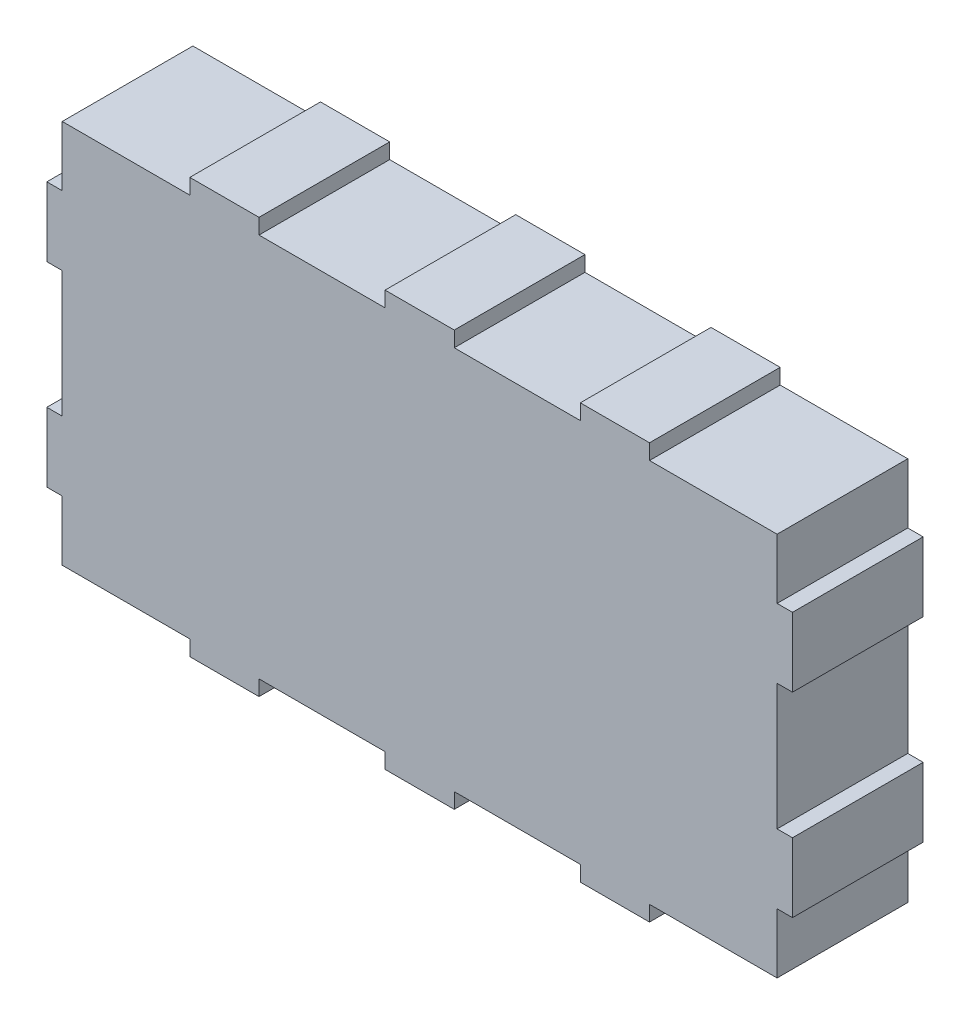
SolidWorks part; units mm, degrees
ref_plane "前视基准面" through (0, 0, 0) normal (0, 0, 1) x (1, 0, 0)
ref_plane "上视基准面" through (0, 0, 0) normal (0, 1, 0) x (1, 0, 0)
ref_plane "右视基准面" through (0, 0, 0) normal (1, 0, 0) x (0, 0, -1)
sketch "草图1" plane through (0, 0, 0) normal (0, 0, 1) x (1, 0, 0)
  line L0 (-4.85, 1.72) -> (-4.65, 1.72)
  line L1 (-4.65, 1.72) -> (-4.65, 2.5)
  line L2 (-4.65, 2.5) -> (-2.99, 2.5)
  line L3 (-2.99, 2.5) -> (-2.99, 2.7)
  line L4 (-2.99, 2.7) -> (-2.09, 2.7)
  line L5 (-2.09, 2.7) -> (-2.09, 2.5)
  line L6 (-2.09, 2.5) -> (-0.45, 2.5)
  line L7 (-0.45, 2.5) -> (-0.45, 2.7)
  line L8 (-0.45, 2.7) -> (0.45, 2.7)
  line L9 (0.45, 2.7) -> (0.45, 2.5)
  line L10 (0.45, 2.5) -> (2.09, 2.5)
  line L11 (2.09, 2.5) -> (2.09, 2.7)
  line L12 (2.09, 2.7) -> (2.99, 2.7)
  line L13 (2.99, 2.7) -> (2.99, 2.5)
  line L14 (2.99, 2.5) -> (4.65, 2.5)
  line L15 (4.65, 2.5) -> (4.65, 1.72)
  line L16 (4.65, 1.72) -> (4.85, 1.72)
  line L17 (4.85, 1.72) -> (4.85, 0.82)
  line L18 (4.85, 0.82) -> (4.65, 0.82)
  line L19 (4.65, 0.82) -> (4.65, -0.82)
  line L20 (4.65, -0.82) -> (4.85, -0.82)
  line L21 (4.85, -0.82) -> (4.85, -1.72)
  line L22 (4.85, -1.72) -> (4.65, -1.72)
  line L23 (4.65, -1.72) -> (4.65, -2.5)
  line L24 (4.65, -2.5) -> (2.99, -2.5)
  line L25 (2.99, -2.5) -> (2.99, -2.7)
  line L26 (2.99, -2.7) -> (2.09, -2.7)
  line L27 (2.09, -2.7) -> (2.09, -2.5)
  line L28 (2.09, -2.5) -> (0.45, -2.5)
  line L29 (0.45, -2.5) -> (0.45, -2.7)
  line L30 (0.45, -2.7) -> (-0.45, -2.7)
  line L31 (-0.45, -2.7) -> (-0.45, -2.5)
  line L32 (-0.45, -2.5) -> (-2.09, -2.5)
  line L33 (-2.09, -2.5) -> (-2.09, -2.7)
  line L34 (-2.09, -2.7) -> (-2.99, -2.7)
  line L35 (-2.99, -2.7) -> (-2.99, -2.5)
  line L36 (-2.99, -2.5) -> (-3, -2.5)
  line L37 (-3, -2.5) -> (-4.65, -2.5)
  line L38 (-4.65, -2.5) -> (-4.65, -1.72)
  line L39 (-4.65, -1.72) -> (-4.85, -1.72)
  line L40 (-4.85, -1.72) -> (-4.85, -0.82)
  line L41 (-4.85, -0.82) -> (-4.65, -0.82)
  line L42 (-4.65, -0.82) -> (-4.65, 0.82)
  line L43 (-4.65, 0.82) -> (-4.85, 0.82)
  line L44 (-4.85, 0.82) -> (-4.85, 1.72)
extrude "Component_Outline" add sketch "草图1" along normal blind 1.7 separate body
sketch3d "3D草图1"
  line L0 (0, 0, 0) -> (1, 0, 0)
  line L1 (0, 0, 0) -> (0, 1, 0)
  line L2 (0, 0, 0) -> (0, 0, 1)
  point P0 (0, 0, 0)
